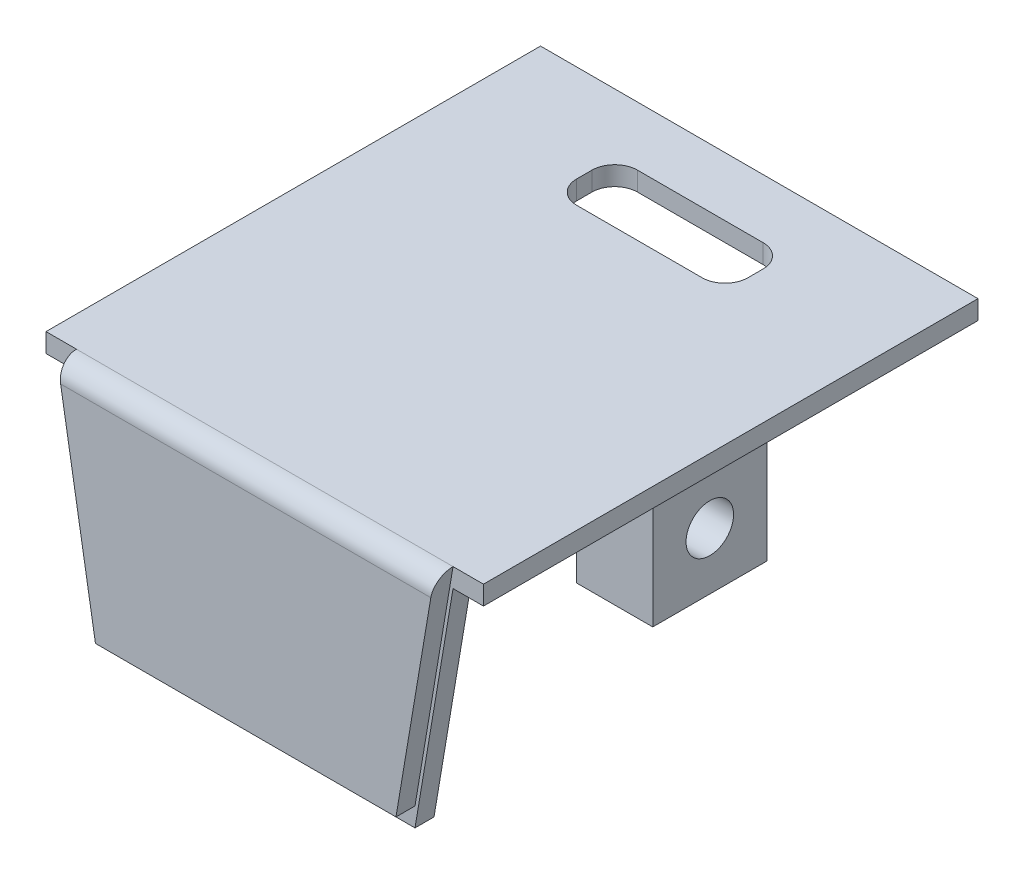
SolidWorks part; units mm, degrees
ref_plane "Ebene vorne" through (0, 0, 0) normal (0, 0, 1) x (1, 0, 0)
ref_plane "Ebene oben" through (0, 0, 0) normal (0, 1, 0) x (1, 0, 0)
ref_plane "Ebene rechts" through (0, 0, 0) normal (1, 0, 0) x (0, 0, -1)
sketch "Skizze1" plane through (0, 0, 0) normal (0, 1, 0) x (1, 0, 0)
  line L2 (11.5, -13) -> (11.5, 13)
  line L3 (11.5, 13) -> (-11.5, 13)
  line L4 (-11.5, -13) -> (-11.5, 13)
  line L5 (11.5, -13) -> (-11.5, 13) construction
  line L6 (11.5, 13) -> (-11.5, -13) construction
  line L10 (-11.5, -13) -> (11.5, -13)
  point P0 (0, 0)
  point P9 (0, -8.4)
  dimension "D1" = 23
  dimension "D2" = 26
  dimension "D5" = 0
extrude "Aufsatz-Linear austragen1" add sketch "Skizze1" along normal blind 1
sketch "Skizze2" plane through (0, 0, 0) normal (0, -1, 0) x (1, 0, 0)
  line L0 (11.5, 13) -> (11.5, -13) construction
  line L1 (6.4, -3) -> (10.4, -3)
  line L2 (6.4, -3) -> (6.4, 3)
  line L3 (6.4, 3) -> (10.4, 3)
  line L4 (10.4, -3) -> (10.4, 3)
  line L5 (6.4, -3) -> (10.4, 3) construction
  line L6 (6.4, 3) -> (10.4, -3) construction
  line L7 (0, 0) -> (0, 6.8035) construction
  point P0 (8.4, 0)
  dimension "D1" = 6
  dimension "D2" = 3
  dimension "D3" = 1.1
  dimension "D4" = 4
extrude "Aufsatz-Linear austragen2" add sketch "Skizze2" along normal blind 6.5
sketch "Skizze3" plane through (10.4, 0, 0) normal (1, 0, 0) x (0, 0, -1)
  line L0 (-13, 1) -> (13, 1) construction
  line L1 (3, -6.5) -> (3, 0) construction
  circle A0 centre (0, -3.5) radius 1.25
  dimension "D1" = 4.5
  dimension "D2" = 2.5
  dimension "D3" = 3
extrude "Schnitt-Linear austragen1" cut sketch "Skizze3" against normal up to surface (4 mm away) up to face at (6.4, -3.25, 0)
mirror "Spiegeln1" about plane through (0, 0, 0) normal (1, 0, 0) of "Schnitt-Linear austragen1", "Aufsatz-Linear austragen2"
sketch "Skizze4" plane through (0, 0, 13) normal (0, 0, 1) x (1, 0, 0)
  line L0 (9.9, 1) -> (-9.9, 1)
  line L1 (-11.5, 1) -> (11.5, 1) construction
  line L2 (-9.9, 1) -> (-7.9, -10.9)
  line L3 (-7.9, -10.9) -> (7.9, -10.9)
  line L4 (0, 0) -> (0, -14.025) construction
  line L5 (-11.5, 0) -> (11.5, 0) construction
  line L6 (9.9, 1) -> (7.9, -10.9)
  point P11 (0, -10.9)
  point P12 (0, 1)
  dimension "D1" = 9.9
  dimension "D2" = 11.9
  dimension "D3" = 7.9
extrude "Aufsatz-Linear austragen3" add sketch "Skizze4" along normal blind 1
sketch "Skizze5" plane through (0, 0, 13) normal (0, 0, -1) x (-1, 0, 0)
  line L0 (-7.9, -10.9) -> (-7.9, -11.9) construction
  line L1 (-7.9, -11.9) -> (7.9, -11.9)
  line L2 (-7.9, -10.9) -> (-9.7319, 0) construction
  line L3 (-7.9, -11.9) -> (-9.9, 0)
  line L4 (-9.7319, 0) -> (-11.5, 0) construction
  line L5 (-9.9, 0) -> (9.9, 0)
  line L6 (0, 0) -> (0, -13.243) construction
  line L7 (7.9, -10.9) -> (7.9, -11.9) construction
  line L8 (7.9, -11.9) -> (9.9, 0)
  point P17 (0, -11.9)
  dimension "D2" = 1
extrude "Aufsatz-Linear austragen4" add sketch "Skizze5" along normal blind 1
sketch "Skizze6" plane through (0, 1, 0) normal (0, 1, 0) x (1, 0, 0)
  line L0 (0, 0) -> (0, 8.3) construction
  line L1 (11.5, 13) -> (-11.5, 13) construction
  line L2 (3.3, 9.9) -> (-3.3, 9.9)
  line L3 (4.5, 8.7) -> (4.5, 7.9)
  line L4 (3.3, 6.7) -> (-3.3, 6.7)
  line L5 (-4.5, 8.7) -> (-4.5, 7.9)
  line L6 (4.5, 9.9) -> (-4.5, 6.7) construction
  line L7 (4.5, 6.7) -> (-4.5, 9.9) construction
  arc A0 (4.5, 7.9) -> (3.3, 6.7) centre (3.3, 7.9) cw
  arc A1 (3.3, 9.9) -> (4.5, 8.7) centre (3.3, 8.7) cw
  arc A2 (-3.3, 9.9) -> (-4.5, 8.7) centre (-3.3, 8.7) ccw
  arc A3 (-3.3, 6.7) -> (-4.5, 7.9) centre (-3.3, 7.9) cw
  point P7 (0, 10.3561)
  dimension "D3" = 1.2
  dimension "D1" = 3.2
  dimension "D2" = 9
  dimension "D4" = 3.1
extrude "Schnitt-Linear austragen2" cut sketch "Skizze6" against normal up to surface (1 mm away) up to face at (8.4, 0, 0)
fillet "Verrundung1" radius 1 1 edges at (0, 1, 14)
